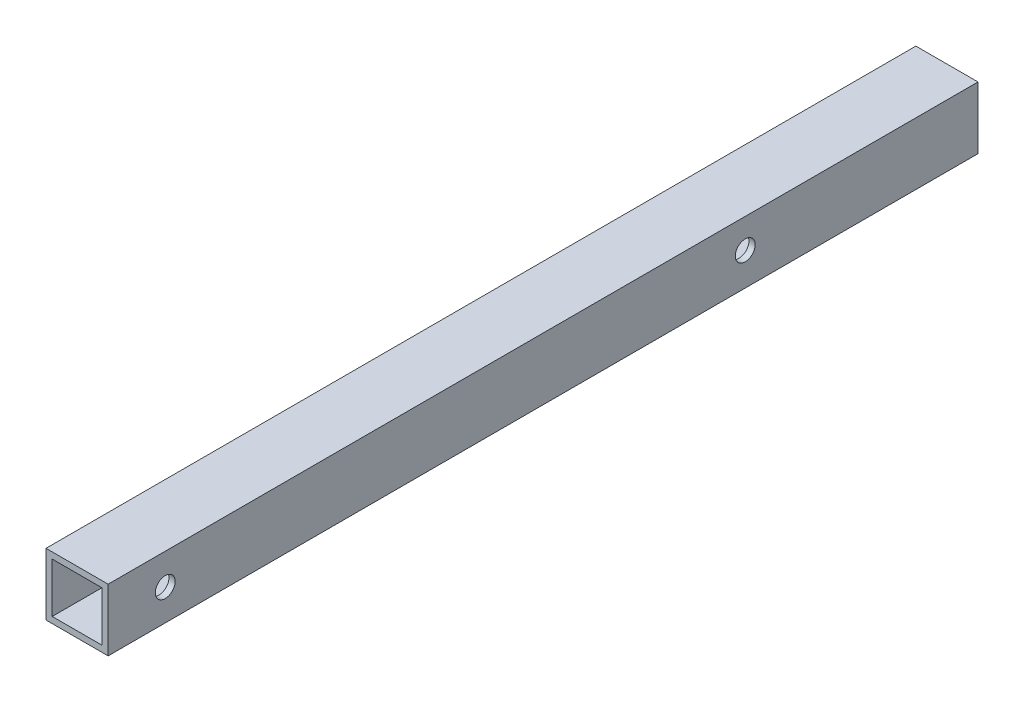
SolidWorks part; units mm, degrees
ref_plane "正面" through (0, 0, 0) normal (0, 0, 1) x (1, 0, 0)
ref_plane "平面" through (0, 0, 0) normal (0, 1, 0) x (1, 0, 0)
ref_plane "右側面" through (0, 0, 0) normal (1, 0, 0) x (0, 0, -1)
sketch "ｽｹｯﾁ1" plane through (0, 0, 0) normal (0, 0, 1) x (1, 0, 0)
  line L0 (-4, 4) -> (-4, -4)
  line L1 (-5, 5) -> (5, 5)
  line L2 (-5, 5) -> (-5, -5)
  line L3 (-5, -5) -> (5, -5)
  line L4 (5, 5) -> (5, -5)
  line L5 (-5, 5) -> (5, -5) construction
  line L6 (-5, -5) -> (5, 5) construction
  line L7 (-4, -4) -> (4, -4)
  line L8 (4, 4) -> (4, -4)
  line L9 (-4, 4) -> (4, 4)
  point P0 (0, 0)
  dimension "D1" = 10
  dimension "D2" = 10
  dimension "D3" = 1
extrude "ﾎﾞｽ - 押し出し1" add sketch "ｽｹｯﾁ1" along normal blind 140
sketch "ｽｹｯﾁ2" plane through (5, 0, 0) normal (1, 0, 0) x (0, 0, -1)
  line L0 (5.5, 0) -> (-5.5, 0) construction
  line L1 (0, 5.5) -> (0, -5.5) construction
  circle A0 centre (-130.81, 0) radius 1.6
  dimension "D1" = 3.2
  dimension "D2" = 130.81
extrude "ｶｯﾄ - 押し出し1" cut sketch "ｽｹｯﾁ2" against normal through all
sketch "ｽｹｯﾁ3" plane through (5, 0, 0) normal (1, 0, 0) x (0, 0, -1)
  line L0 (-130.81, 0) -> (0.0043, 0.3623) construction
  circle A0 centre (-37.4651, 0.2585) radius 1.6
extrude "ｶｯﾄ - 押し出し2" cut sketch "ｽｹｯﾁ3" against normal through all
